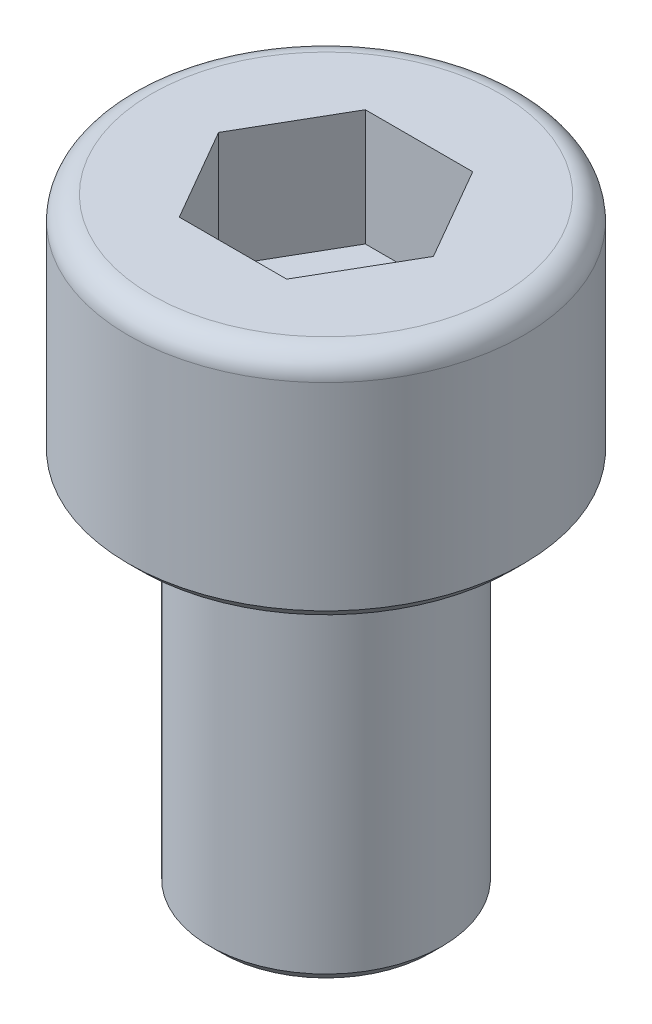
SolidWorks part; units mm, degrees
material "AISI 1045 Steel, cold drawn"
ref_plane "Front Plane" through (0, 0, 0) normal (0, 0, 1) x (1, 0, 0)
ref_plane "Top Plane" through (0, 0, 0) normal (0, 1, 0) x (1, 0, 0)
ref_plane "Right Plane" through (0, 0, 0) normal (1, 0, 0) x (0, 0, -1)
sketch "Sketch1" plane through (0, 0, 0) normal (0, 0, 1) x (1, 0, 0)
  line L0 (0, 0) -> (4.25, 0)
  line L1 (4.25, 0) -> (4.25, -5)
  line L2 (4.25, -5) -> (2.5, -5)
  line L3 (2.5, -5) -> (2.5, -13)
  line L4 (2.5, -13) -> (0, -13)
  line L5 (0, -13) -> (0, 0)
  line L6 (0, -18) -> (0, 5) construction
  dimension "K" = 5
  dimension "D2" = 5
  dimension "L" = 8
  dimension "D4" = 5
  dimension "D" = 5
  dimension "DK" = 8.5
revolve "Revolve1" add sketch "Sketch1" angle 360 about L6
sketch "Sketch2" plane through (0, 0, 0) normal (0, 1, 0) x (1, 0, 0)
  line L1 (2.3094, 0) -> (1.1547, 2)
  line L2 (1.1547, 2) -> (-1.1547, 2)
  line L3 (-1.1547, 2) -> (-2.3094, 0)
  line L4 (-2.3094, 0) -> (-1.1547, -2)
  line L5 (-1.1547, -2) -> (1.1547, -2)
  line L6 (1.1547, -2) -> (2.3094, 0)
  circle A0 centre (0, 0) radius 2 construction
  point P1 (0, 0)
  dimension "D1" = 4
extrude "Cut-Extrude1" cut sketch "Sketch2" against normal blind 2.5
fillet "Fillet1" radius 0.5 1 edges at (4.25, 0, 0)
chamfer "Chamfer1" distance 0.25 angle 45 1 edges at (4.25, -5, 0)
chamfer "Chamfer2" distance 0.25 angle 45 1 edges at (2.5, -13, 0)
cosmetic thread "Cosmetic Thread1" parameters "ThreadLength"=5.6, "D2"=4.11
